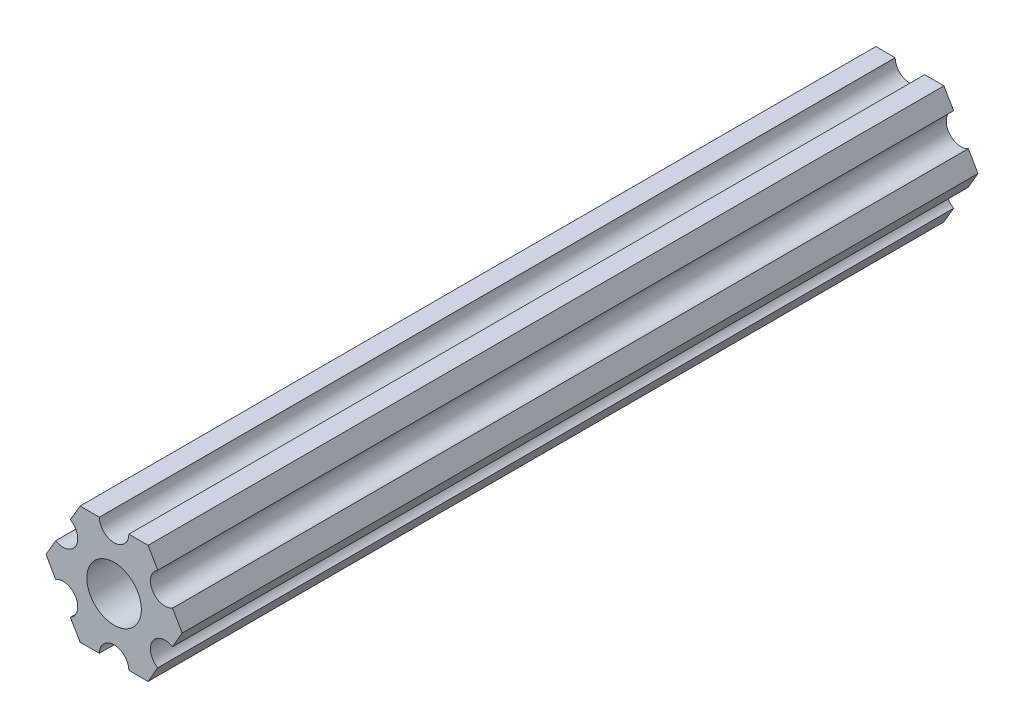
SolidWorks part; units mm, degrees
material "6061 Alloy"
ref_plane "Front Plane" through (0, 0, 0) normal (0, 0, 1) x (1, 0, 0)
ref_plane "Top Plane" through (0, 0, 0) normal (0, 1, 0) x (1, 0, 0)
ref_plane "Right Plane" through (0, 0, 0) normal (1, 0, 0) x (0, 0, -1)
ref_plane "Plane1" through (0, 0, 304.8) normal (0, 0, 1) x (1, 0, 0)
sketch "Sketch1" plane through (0, 0, 304.8) normal (0, 0, 1) x (1, 0, 0)
  line L0 (6.293, -1.8002) -> (7.3323, 0)
  line L1 (7.3323, 0) -> (6.293, 1.8002)
  line L2 (4.7055, 4.5498) -> (3.6662, 6.35)
  line L3 (3.6662, 6.35) -> (1.5875, 6.35)
  line L4 (-1.5875, 6.35) -> (-3.6662, 6.35)
  line L5 (-3.6662, 6.35) -> (-4.7055, 4.5498)
  line L6 (-6.293, 1.8002) -> (-7.3323, 0)
  line L7 (-7.3323, 0) -> (-6.293, -1.8002)
  line L8 (-4.7055, -4.5498) -> (-3.6662, -6.35)
  line L9 (-3.6662, -6.35) -> (-1.5875, -6.35)
  line L10 (1.5875, -6.35) -> (3.6662, -6.35)
  line L11 (3.6662, -6.35) -> (4.7055, -4.5498)
  arc A0 (6.293, 1.8002) -> (4.7055, 4.5498) centre (5.4993, 3.175) cw
  arc A1 (1.5875, 6.35) -> (-1.5875, 6.35) centre (0, 6.35) cw
  arc A2 (-4.7055, 4.5498) -> (-6.293, 1.8002) centre (-5.4993, 3.175) cw
  arc A3 (-6.293, -1.8002) -> (-4.7055, -4.5498) centre (-5.4993, -3.175) cw
  arc A4 (-1.5875, -6.35) -> (1.5875, -6.35) centre (0, -6.35) cw
  arc A5 (4.7055, -4.5498) -> (6.293, -1.8002) centre (5.4993, -3.175) cw
  circle A6 centre (0, 0) radius 2.9337
extrude "Boss-Extrude1" add sketch "Sketch1" against normal blind 85.725
